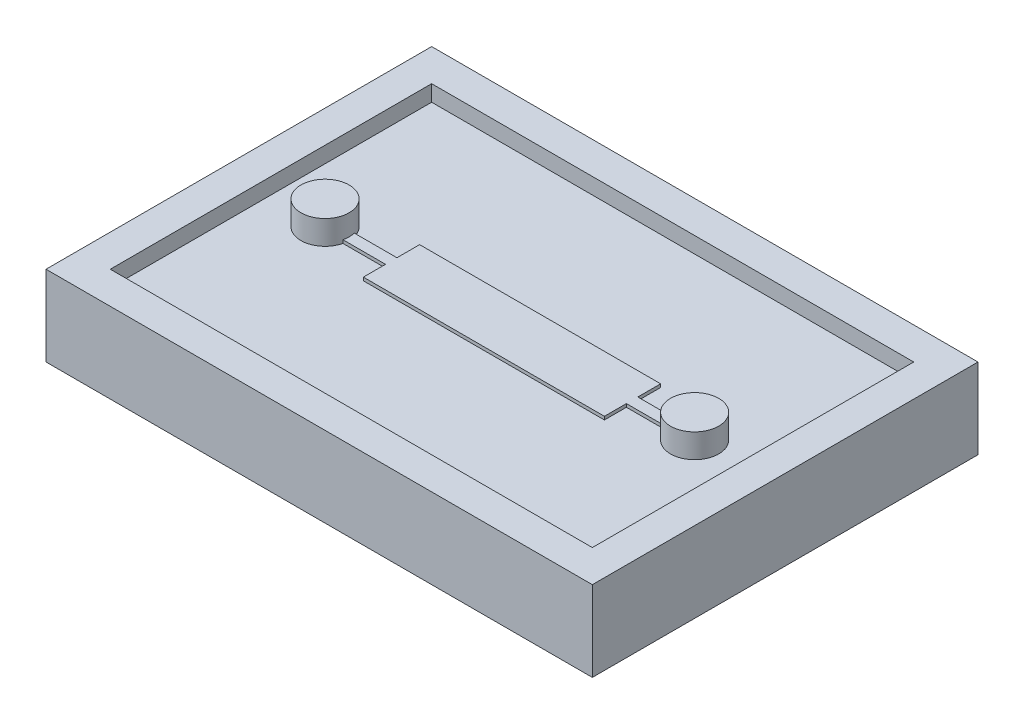
SolidWorks part; units mm, degrees
ref_plane "Alzado" through (0, 0, 0) normal (0, 0, 1) x (1, 0, 0)
ref_plane "Planta" through (0, 0, 0) normal (0, 1, 0) x (1, 0, 0)
ref_plane "Vista lateral" through (0, 0, 0) normal (1, 0, 0) x (0, 0, -1)
sketch "Croquis1" plane through (0, 0, 0) normal (0, 1, 0) x (1, 0, 0)
  line L1 (-17, 12) -> (17, 12)
  line L2 (-17, 12) -> (-17, -12)
  line L3 (-17, -12) -> (17, -12)
  line L4 (17, 12) -> (17, -12)
  line L5 (-17, 12) -> (17, -12) construction
  line L6 (-17, -12) -> (17, 12) construction
  point P0 (0, 0)
  dimension "D1" = 34
  dimension "D2" = 24
extrude "Saliente-Extruir1" add sketch "Croquis1" along normal blind 3
sketch "Croquis2" plane through (0, 3, 0) normal (0, 1, 0) x (1, 0, 0)
  line L1 (-15, 10) -> (15, 10)
  line L2 (-15, 10) -> (-15, -10)
  line L3 (-15, -10) -> (15, -10)
  line L4 (15, 10) -> (15, -10)
  line L5 (-15, 10) -> (15, -10) construction
  line L6 (-15, -10) -> (15, 10) construction
  point P0 (0, 0)
  dimension "D1" = 30
  dimension "D2" = 20
extrude "Cortar-Extruir1" cut sketch "Croquis2" against normal blind 1
sketch "Croquis3" plane through (0, 2, 0) normal (0, 1, 0) x (1, 0, 0)
  line L0 (0, 10) -> (0, -10) construction
  line L1 (15, 10) -> (-15, 10) construction
  line L2 (-15, -10) -> (15, -10) construction
  line L3 (-15, 0) -> (15, 0) construction
  line L4 (-15, 10) -> (-15, -10) construction
  line L5 (15, -10) -> (15, 10) construction
  line L6 (-9, 10) -> (-9, -10) construction
  line L7 (15, 10) -> (-15, 10) construction
  line L8 (9, 10) -> (9, -10) construction
  line L9 (-15, 4) -> (15, 4) construction
  line L10 (15, -10) -> (15, 10) construction
  line L11 (-15, -4) -> (15, -4) construction
  line L12 (-15, 10) -> (-15, -10) construction
  line L13 (-15, -10) -> (15, -10) construction
  dimension "D1" = 6
  dimension "D2" = 6
  dimension "D3" = 6
  dimension "D4" = 6
sketch "Croquis6" plane through (-1.7553, 2, -0.1099) normal (0, 1, 0) x (1, 0, 0)
  circle A0 centre (-9.8547, -0.135) radius 1.5
extrude "Saliente-Extruir3" add sketch "Croquis6" along normal blind 1.5
pattern_linear "MatrizL1" count 2 spacing 23 along (1, 0, 0) of "Saliente-Extruir3"
sketch "Croquis8" plane through (0, 2, 0.5129) normal (0, 1, 0) x (1, 0, 0)
  line L0 (-6.6756, 0.8523) -> (-6.6756, 0.1423)
  line L1 (-6.6756, 0.8523) -> (-11.6756, 0.8523)
  line L2 (-6.6756, 0.1423) -> (-11.6756, 0.1423)
  line L3 (-11.6756, 0.8523) -> (-11.6756, 0.1423)
  dimension "D1" = 0.71
  dimension "D2" = 5
extrude "Saliente-Extruir5" add sketch "Croquis8" along normal blind 0.2
sketch "Croquis9" plane through (0, 2, 0) normal (0, 1, 0) x (1, 0, 0)
  line L0 (9, 4) -> (9, -6.4828)
  line L1 (9, 4) -> (3.9883, 4)
  line L2 (9, -6.4828) -> (3.9883, -6.4828)
  line L3 (3.9883, 4) -> (3.9883, -6.4828)
  line L4 (9, 10) -> (9, -10) construction
  line L5 (-15, 4) -> (15, 4) construction
  line L6 (3.9883, 4) -> (9, -6.4828) construction
  line L7 (9, 4) -> (3.9883, -6.4828) construction
  line L8 (6.4941, 4) -> (6.4941, -6.4828) construction
sketch "Croquis10" plane through (3.6392, 2, -0.5129) normal (0, 1, 0) x (1, 0, 0)
  line L0 (2.9903, -0.8935) -> (2.9903, -0.1835)
  line L1 (2.9903, -0.8935) -> (7.9903, -0.8935)
  line L2 (2.9903, -0.1835) -> (7.9903, -0.1835)
  line L3 (7.9903, -0.8935) -> (7.9903, -0.1835)
  dimension "D1" = 0.71
  dimension "D2" = 5
extrude "Saliente-Extruir6" add sketch "Croquis10" along normal blind 0.2
sketch "Croquis14" plane through (0, 3, 0) normal (0, 1, 0) x (1, 0, 0)
  line L0 (0, 12) -> (0, -12) construction
  line L1 (17, 12) -> (-17, 12) construction
  line L2 (-17, -12) -> (17, -12) construction
  line L3 (17, 0) -> (-17, 0) construction
  line L4 (17, -12) -> (17, 12) construction
  line L5 (-17, 12) -> (-17, -12) construction
  line L7 (-7.5, 1.75) -> (7.5, 1.75)
  line L8 (-7.5, 1.75) -> (-7.5, -1.75)
  line L9 (-7.5, -1.75) -> (7.5, -1.75)
  line L10 (7.5, 1.75) -> (7.5, -1.75)
  line L11 (-7.5, 1.75) -> (7.5, -1.75) construction
  line L12 (-7.5, -1.75) -> (7.5, 1.75) construction
  point P12 (0, 0)
  dimension "D1" = 15
  dimension "D2" = 3.5
sketch "Croquis18" plane through (0, 2, 0) normal (0, 1, 0) x (1, 0, 0)
  line L7 (-7.5, 1.75) -> (7.5, 1.75)
  line L8 (-7.5, 1.75) -> (-7.5, -1.75)
  line L9 (-7.5, -1.75) -> (7.5, -1.75)
  line L10 (7.5, 1.75) -> (7.5, -1.75)
  line L11 (-7.5, 1.75) -> (7.5, -1.75) construction
  line L12 (-7.5, -1.75) -> (7.5, 1.75) construction
  point P12 (0, 0)
  dimension "D1" = 15
  dimension "D2" = 3.5
extrude "Saliente-Extruir8" add sketch "Croquis18" along normal blind 0.2
sketch "Croquis23" plane through (0, 0, 0) normal (0, -1, 0) x (1, 0, 0)
  line L1 (-17, 12) -> (17, 12)
  line L2 (-17, 12) -> (-17, -12)
  line L3 (-17, -12) -> (17, -12)
  line L4 (17, 12) -> (17, -12)
  line L5 (-17, 12) -> (17, -12) construction
  line L6 (-17, -12) -> (17, 12) construction
  point P0 (0, 0)
extrude "Saliente-Extruir11" add sketch "Croquis23" along normal blind 2
